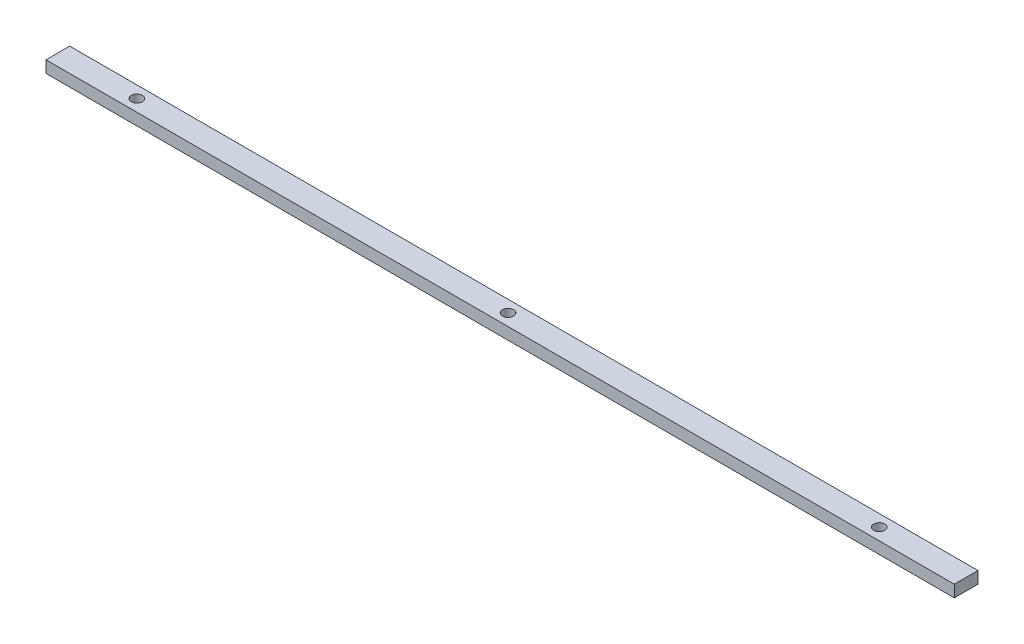
SolidWorks part; units mm, degrees
material "AISI 1035 Сталь (SS)"
ref_plane "Спереди" through (0, 0, 0) normal (0, 0, 1) x (1, 0, 0)
ref_plane "Сверху" through (0, 0, 0) normal (0, 1, 0) x (1, 0, 0)
ref_plane "Справа" through (0, 0, 0) normal (1, 0, 0) x (0, 0, -1)
sketch "Эскиз1" plane through (0, 0, 0) normal (0, 0, 1) x (1, 0, 0)
  line L1 (44.0503, 37.6311) -> (1194.0503, 37.6311)
  line L2 (44.0503, 37.6311) -> (44.0503, 22.6311)
  line L3 (44.0503, 22.6311) -> (1194.0503, 22.6311)
  line L4 (1194.0503, 37.6311) -> (1194.0503, 22.6311)
  dimension "D1" = 1150
  dimension "D2" = 15
extrude "Бобышка-Вытянуть1" add sketch "Эскиз1" along normal blind 30
sketch "Эскиз2" plane through (0, 37.6311, 0) normal (0, 1, 0) x (1, 0, 0)
  line L2 (44.0503, -30) -> (44.0503, 0) construction
  circle A0 centre (144.0503, -15) radius 7
  circle A1 centre (614.0503, -15) radius 7
  circle A2 centre (1084.0503, -15) radius 7
  point P10 (44.0503, -15)
  dimension "D1" = 14
  dimension "D2" = 100
  dimension "D3" = 3
extrude "Вырез-Вытянуть1" cut sketch "Эскиз2" against normal through all
